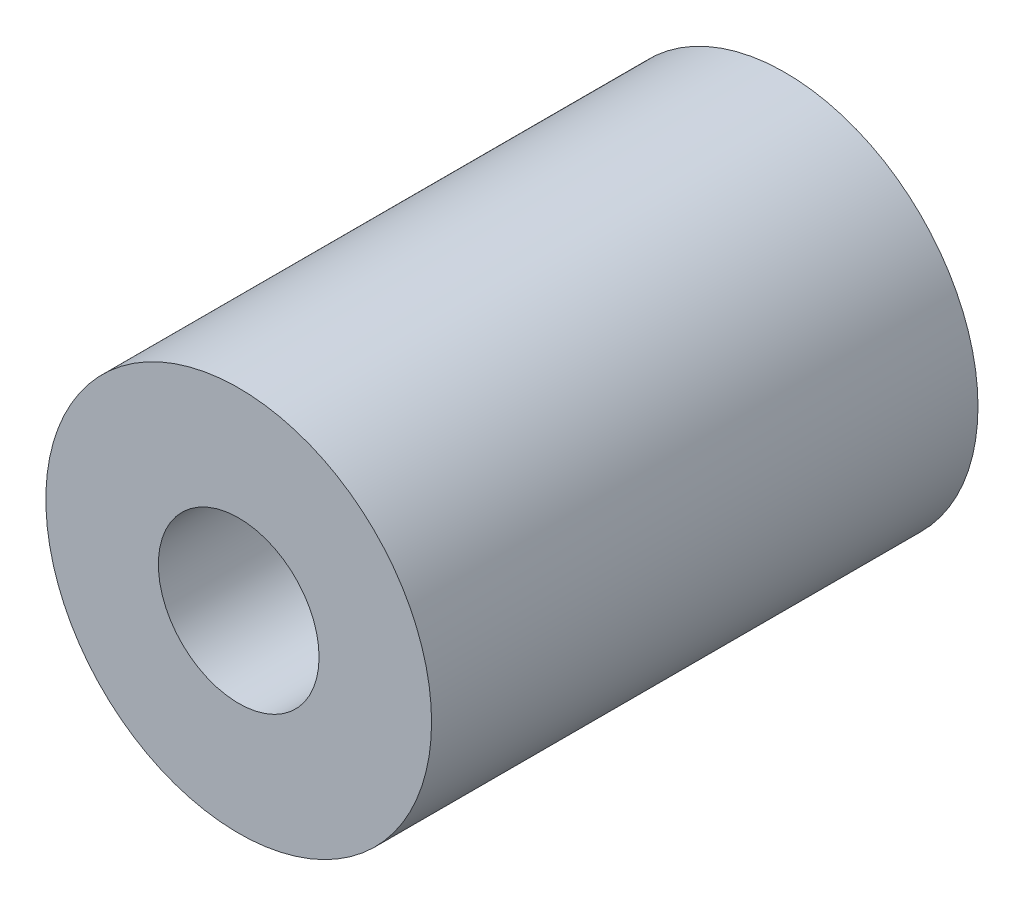
SolidWorks part; units mm, degrees
material "6063-T5"
ref_plane "正面" through (0, 0, 0) normal (0, 0, 1) x (1, 0, 0)
ref_plane "平面" through (0, 0, 0) normal (0, 1, 0) x (1, 0, 0)
ref_plane "右側面" through (0, 0, 0) normal (1, 0, 0) x (0, 0, -1)
sketch "ｽｹｯﾁ1" plane through (0, 0, 0) normal (0, 0, 1) x (1, 0, 0)
  circle A0 centre (0, 0) radius 3
  circle A1 centre (0, 0) radius 1.25
  dimension "D1" = 6
  dimension "D2" = 2.5
extrude "ﾎﾞｽ - 押し出し1" add sketch "ｽｹｯﾁ1" along normal blind 8.5
